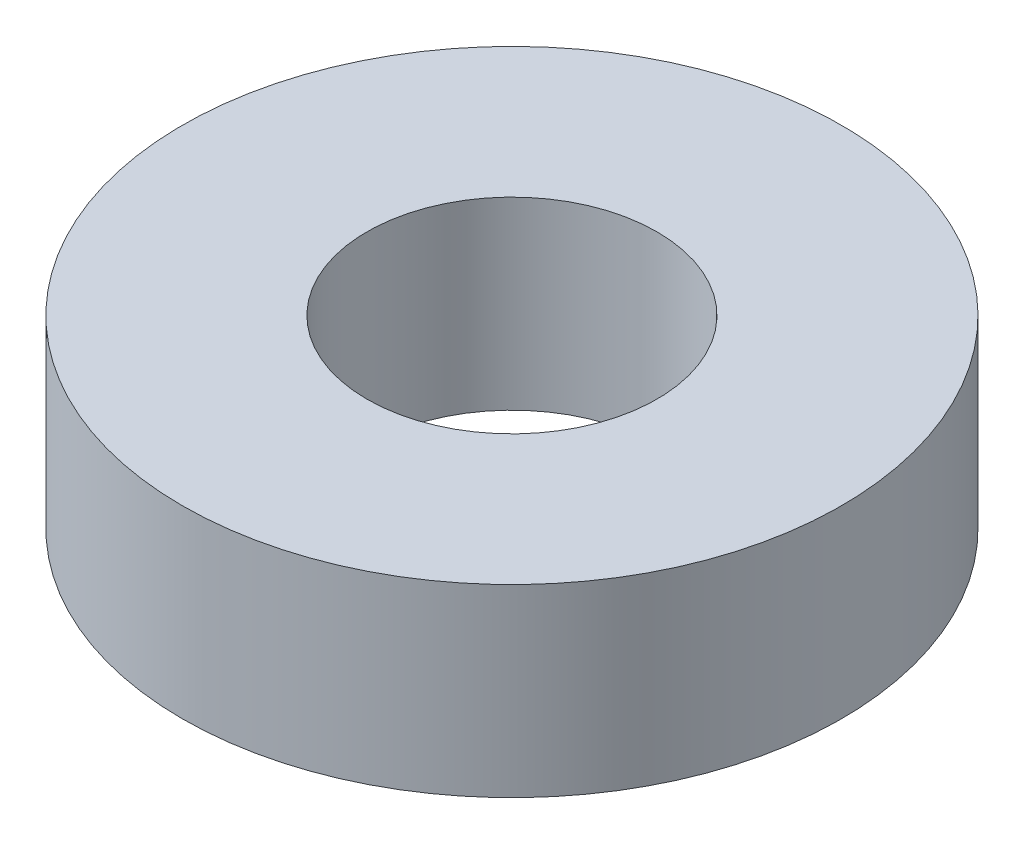
SolidWorks part; units mm, degrees
ref_plane "Alzado" through (0, 0, 0) normal (0, 0, 1) x (1, 0, 0)
ref_plane "Planta" through (0, 0, 0) normal (0, 1, 0) x (1, 0, 0)
ref_plane "Vista lateral" through (0, 0, 0) normal (1, 0, 0) x (0, 0, -1)
sketch "Croquis1" plane through (0, 0, 0) normal (0, 1, 0) x (1, 0, 0)
  circle A0 centre (0, 0) radius 50
  circle A1 centre (0, 0) radius 22
  dimension "D1" = 100
  dimension "D2" = 28
extrude "Saliente-Extruir1" add sketch "Croquis1" along normal blind 28
